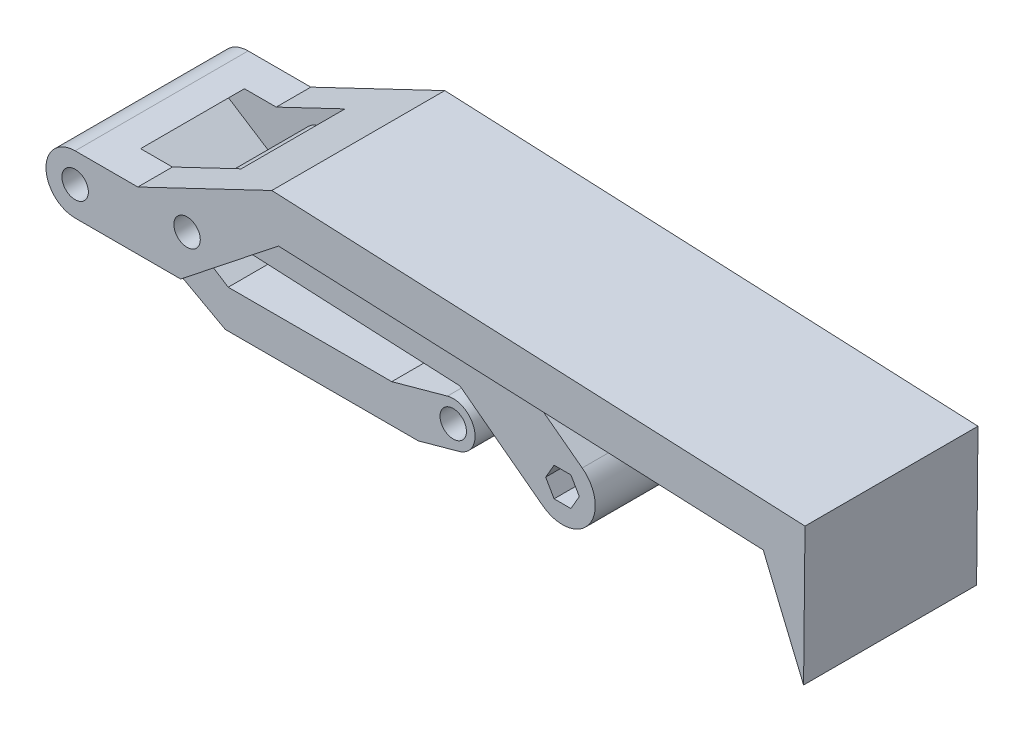
SolidWorks part; units mm, degrees
other "Follower Link"
other "Drive Link"
ref_plane "Front Plane" through (0, 0, 0) normal (0, 0, 1) x (1, 0, 0)
ref_plane "Top Plane" through (0, 0, 0) normal (0, 1, 0) x (1, 0, 0)
ref_plane "Right Plane" through (0, 0, 0) normal (1, 0, 0) x (0, 0, -1)
sketch "Sketch1" plane through (0, 0, 0) normal (0, 0, 1) x (1, 0, 0)
  line L0 (-6.4738, -12.5) -> (58.3471, -12.5) construction
  line L2 (15, -15) -> (-15, -15) construction
  line L3 (15, -15) -> (15, 15) construction
  line L4 (15, 15) -> (-15, 15) construction
  line L5 (-15, -15) -> (-15, 15) construction
  line L6 (15, -15) -> (-15, 15) construction
  line L7 (15, 15) -> (-15, -15) construction
  line L9 (96.2216, -5.085) -> (96.2216, 32.1225) construction
  line L10 (0, 0) -> (-85.5521, 41.3019)
  line L11 (-30, 0) -> (-116.4877, 39.305)
  line L12 (-116.4877, 39.305) -> (-85.5521, 41.3019)
  circle A0 centre (0, 0) radius 12.5 construction
  line B0 (-85.5521, 41.3019) -> (34.321, 46.8209)
  line B1 (34.321, 46.8209) -> (53.9024, 30.3388)
  dimension "D1" = 25
  dimension "D4" = 95
  dimension "D3" = 30
  dimension "D5" = 95
  dimension "D7" = 30
sketch_block_instance "Block1-1"
sketch_block "Block1" parameters "D1"=25.1294, "D2"=99.8862
sketch "Sketch5" plane through (0, 0, 0) normal (0, 0, 1) x (1, 0, 0)
  line L0 (0, 0) -> (-93.0726, 19.0392) construction
  line L1 (-30, 0) -> (-123.8083, 15) construction
  line L2 (-123.8083, 15) -> (-93.0726, 19.0392) construction
  line L3 (-30, 0) -> (-116.4877, 39.305) construction
  line L4 (0, 0) -> (-85.5521, 41.3019) construction
  line L5 (-116.4877, 39.305) -> (-85.5521, 41.3019) construction
  line L6 (-31.5923, 5.7849) -> (-28.4077, -5.7849) construction
  line L7 (-120.9347, 20.2671) -> (-91.785, 1.5769)
  line L8 (-46.8797, 1.5769) -> (-31.5923, 5.7849)
  line L9 (-126.6819, 9.7329) -> (-92.5888, -8.8677)
  line L10 (-39.6076, -8.8677) -> (-28.4077, -5.7849)
  line L11 (-5.4117, -7.1912) -> (-28.1515, 9.9213)
  line L12 (-93.3598, 13.0461) -> (-28.1515, 9.9213)
  line L13 (-92.7854, 25.0324) -> (-13.2304, 21.22)
  line L14 (-13.2304, 21.22) -> (5.4117, 7.1912)
  line L15 (-123.8083, 15) -> (-95.429, -1.1532) construction
  line L16 (-95.429, -1.1532) -> (-30, 0) construction
  line L17 (-126.6819, 9.7329) -> (-120.9347, 20.2671) construction
  line L18 (-5.4117, -7.1912) -> (5.4117, 7.1912) construction
  line L19 (-92.7854, 25.0324) -> (-93.3598, 13.0461) construction
  line L20 (-91.785, 1.5769) -> (-46.8797, 1.5769)
  line L21 (4.6188, 0) -> (2.3094, 4)
  line L22 (2.3094, 4) -> (-2.3094, 4)
  line L23 (-2.3094, 4) -> (-4.6188, 0)
  line L24 (-4.6188, 0) -> (-2.3094, -4)
  line L25 (-2.3094, -4) -> (2.3094, -4)
  line L26 (2.3094, -4) -> (4.6188, 0)
  line L27 (-92.5888, -8.8677) -> (-39.6076, -8.8677)
  arc A0 (-92.7854, 25.0324) -> (-93.3598, 13.0461) centre (-93.0726, 19.0392) ccw
  arc A1 (-5.4117, -7.1912) -> (5.4117, 7.1912) centre (0, 0) ccw
  arc A2 (-28.4077, -5.7849) -> (-31.5923, 5.7849) centre (-30, 0) ccw
  arc A4 (-120.9347, 20.2671) -> (-126.6819, 9.7329) centre (-123.8083, 15) ccw
  circle A5 centre (-123.8083, 15) radius 3.6285
  circle A6 centre (-93.0726, 19.0392) radius 3.6285
  circle A7 centre (-30, 0) radius 3.6285
  circle A8 centre (0, 0) radius 4 construction
  point P15 (-44.5387, -8.8677)
  point P36 (-46.8797, 1.5769)
  dimension "D2" = 12
  dimension "D3" = 12
  dimension "D4" = 15
  dimension "D5" = 18
  dimension "D1" = 8
  dimension "D6" = 12
extrude "Boss-Extrude3" add sketch "Sketch5" along normal blind 27.5
ref_plane "Plane1" through (0, 0, 13.75) normal (0, 0, 1) x (1, 0, 0)
sketch "Sketch6" plane through (0, 0, 13.75) normal (0, 0, 1) x (1, 0, 0)
  line L2 (76.1917, -4.029) -> (65.111, 22.551)
  line L3 (-123.8083, 7) -> (-94.8311, 7)
  line L4 (-94.8311, 7) -> (-67.9761, 28.2735)
  line L5 (-67.9761, 28.2735) -> (65.111, 22.551)
  line L6 (-123.8083, 23) -> (-106.597, 23)
  line L7 (-106.597, 23) -> (-69.8134, 40.5641)
  line L8 (-69.8134, 40.5641) -> (76.5795, 33.9637)
  line L9 (76.5795, 33.9637) -> (76.1917, -4.029)
  arc A0 (-123.8083, 23) -> (-123.8083, 7) centre (-123.8083, 15) ccw
  circle A1 centre (-93.0726, 19.0392) radius 3.6285
  circle A2 centre (-123.8083, 15) radius 3.6285
  point P15 (-103.2178, 23.5195)
  point P16 (0, 0)
  point P17 (-94.8311, 8.094)
  dimension "D1" = 200
  dimension "D2" = 8
extrude "Boss-Extrude4" add sketch "Sketch6" along normal offset from surface 10 and the other way offset from surface (23.75 mm away) 10 separate body up to face at (-37.7215, 10.6826, 27.5) offset beyond the face yes other way up to face at (-89.4441, 19.0392, 0)
sketch "Sketch7" plane through (0, 0, 13.75) normal (0, 0, 1) x (1, 0, 0)
  line L0 (-123.3938, 18.9823) -> (-95.5519, 32.8589)
  line L1 (-124.5999, 11.0753) -> (-95.8486, 5.2761)
  arc A0 (-123.3938, 18.9823) -> (-124.5999, 11.0753) centre (-123.8083, 15) ccw
  arc A1 (-95.8486, 5.2761) -> (-95.5519, 32.8589) centre (-93.0726, 19.0392) ccw
extrude "Cut-Extrude2" cut sketch "Sketch7" against normal offset from surface 0.5 and the other way offset from surface (14.25 mm away) 0.5 up to face at (-72.245, 2.4855, 0) offset beyond the face yes other way up to face at (-120.1798, 15, 27.5)
